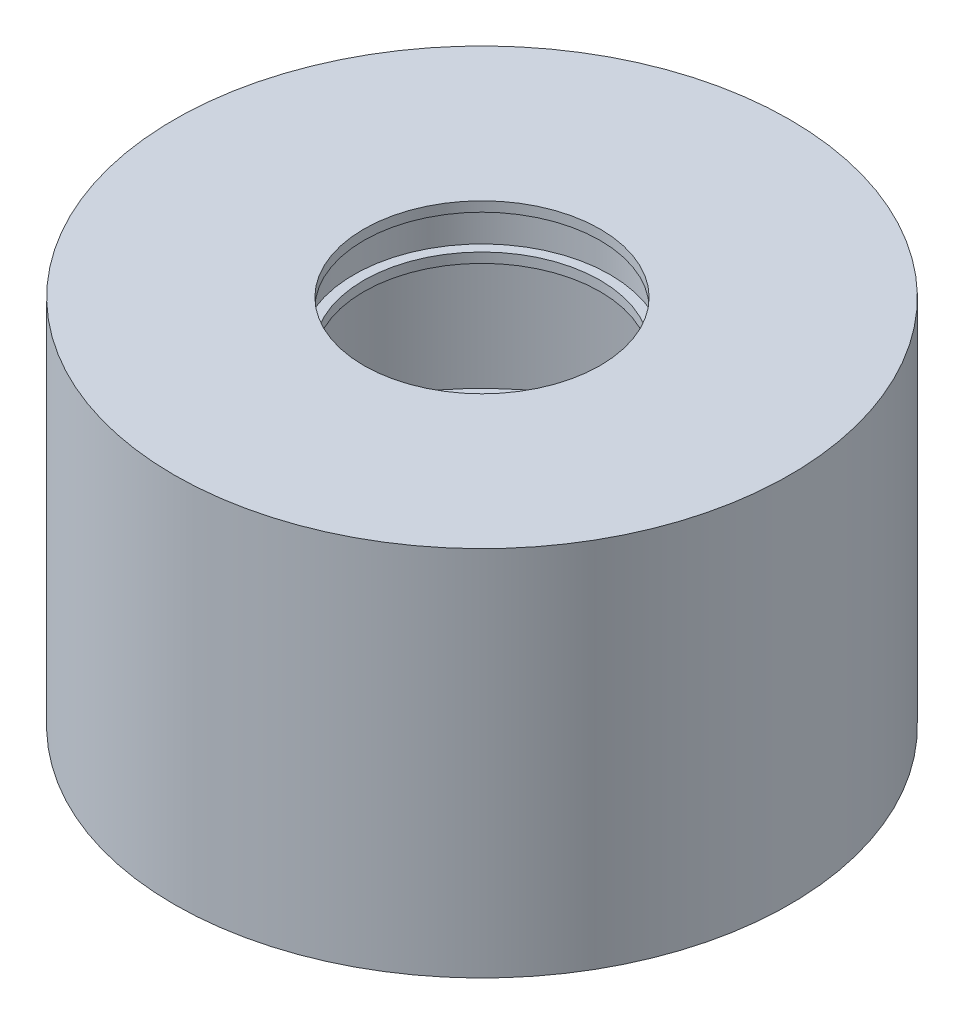
SolidWorks part; units mm, degrees
ref_plane "Front Plane" through (0, 0, 0) normal (0, 0, 1) x (1, 0, 0)
ref_plane "Top Plane" through (0, 0, 0) normal (0, 1, 0) x (1, 0, 0)
ref_plane "Right Plane" through (0, 0, 0) normal (1, 0, 0) x (0, 0, -1)
sketch "Sketch2" plane through (0, 0, 0) normal (1, 0, 0) x (0, 0, -1)
  line L0 (47, -37.75) -> (62.5, -37.75)
  line L1 (62.5, -37.75) -> (62.5, 37.75)
  line L2 (62.5, 37.75) -> (24, 37.75)
  line L3 (24, 37.75) -> (24, 35.75)
  line L4 (24, 35.75) -> (26, 35.75)
  line L5 (26, 35.75) -> (26, 28.75)
  line L6 (26, 28.75) -> (24, 28.75)
  line L7 (24, 28.75) -> (24, 26.75)
  line L8 (24, 26.75) -> (42.5, 26.75)
  line L11 (47, -25.75) -> (50, -25.75)
  line L12 (50, -25.75) -> (50, -35.75)
  line L13 (50, -35.75) -> (47, -35.75)
  line L14 (47, -35.75) -> (47, -37.75)
  line L15 (47, -25.75) -> (47, -15.75)
  line L17 (53, -15.75) -> (53, 17.75)
  line L18 (0, -15.4373) -> (0, -9.583) construction
  line L19 (0, 0) -> (62.5, 0) construction
  line L20 (47, -15.75) -> (53, -15.75)
  line L21 (42.5, 26.75) -> (42.5, 17.75)
  line L22 (42.5, 17.75) -> (53, 17.75)
  dimension "D1" = 10
  dimension "D2" = 7
  dimension "D3" = 2
  dimension "D4" = 100
  dimension "D5" = 52
  dimension "D6" = 71.5
  dimension "D7" = 125
  dimension "D8" = 2
  dimension "D9" = 3
  dimension "D10" = 106
  dimension "D11" = 10
  dimension "D12" = 85
  dimension "D13" = 20
revolve "Revolve1" add sketch "Sketch2" angle 360 about L18
sketch "Sketch3" plane through (0, -25.75, 0) normal (0, -1, 0) x (1, 0, 0)
  line L0 (-47.5528, 15.4508) -> (0, 0) construction
  line L1 (0, 0) -> (-50, 0) construction
  circle A0 centre (0, 0) radius 50 construction
  circle A1 centre (-47.5528, 15.4508) radius 2
  circle A2 centre (-40.4508, 29.3893) radius 2
  circle A3 centre (-29.3893, 40.4508) radius 2
  circle A4 centre (-15.4508, 47.5528) radius 2
  circle A5 centre (0, 50) radius 2
  circle A6 centre (15.4508, 47.5528) radius 2
  circle A7 centre (29.3893, 40.4508) radius 2
  circle A8 centre (40.4508, 29.3893) radius 2
  circle A9 centre (47.5528, 15.4508) radius 2
  circle A10 centre (50, 0) radius 2
  circle A11 centre (47.5528, -15.4508) radius 2
  circle A12 centre (40.4508, -29.3893) radius 2
  circle A13 centre (29.3893, -40.4508) radius 2
  circle A14 centre (15.4508, -47.5528) radius 2
  circle A15 centre (0, -50) radius 2
  circle A16 centre (-15.4508, -47.5528) radius 2
  circle A17 centre (-29.3893, -40.4508) radius 2
  circle A18 centre (-40.4508, -29.3893) radius 2
  circle A19 centre (-47.5528, -15.4508) radius 2
  circle A20 centre (-50, 0) radius 2
  point P45 (0, 0)
  dimension "D1" = 4
  dimension "D2" = 100
  dimension "D4" = 18
  dimension "D3" = 20
extrude "Cut-Extrude5" cut sketch "Sketch3" against normal blind 50 from offset 2.5 offset against normal yes
